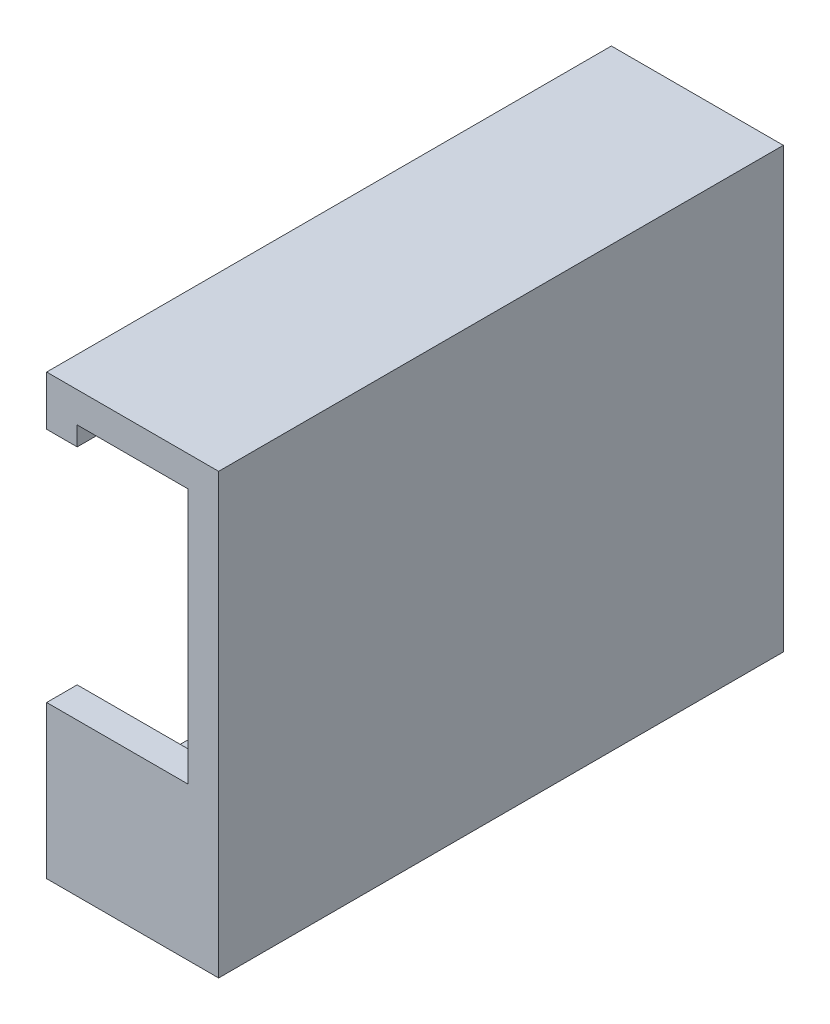
SolidWorks part; units mm, degrees
ref_plane "Front Plane" through (0, 0, 0) normal (0, 0, 1) x (1, 0, 0)
ref_plane "Top Plane" through (0, 0, 0) normal (0, 1, 0) x (1, 0, 0)
ref_plane "Right Plane" through (0, 0, 0) normal (1, 0, 0) x (0, 0, -1)
sketch "Sketch1" plane through (0, 0, 0) normal (0, 0, 1) x (1, 0, 0)
  line L0 (-18.4625, 62.865) -> (0, 62.865)
  line L1 (0, 62.865) -> (0, 0)
  line L2 (0, 0) -> (-18.4625, 0)
  line L3 (-18.4625, 0) -> (-18.4625, 3.175)
  line L4 (-18.4625, 62.865) -> (-18.4625, 59.69)
  dimension "D1" = 62.865
  dimension "D2" = 18.4625
  dimension "D3" = 3.175
extrude "Extrude-Thin1" add sketch "Sketch1" along normal blind 93.98 thin thin type one direction wall 5.08
sketch "Sketch2" plane through (0, 0, 93.98) normal (0, 0, 1) x (1, 0, 0)
  line L1 (-23.5425, 3.175) -> (-23.5425, -5.08) construction
  line L6 (5.08, -5.08) -> (-23.5425, -5.08)
  line L7 (5.08, -5.08) -> (5.08, 20.32)
  line L8 (5.08, 20.32) -> (-23.5425, 20.32)
  line L9 (-23.5425, -5.08) -> (-23.5425, 20.32)
  dimension "D1" = 25.4
extrude "Boss-Extrude1" add sketch "Sketch2" against normal blind 5.08
